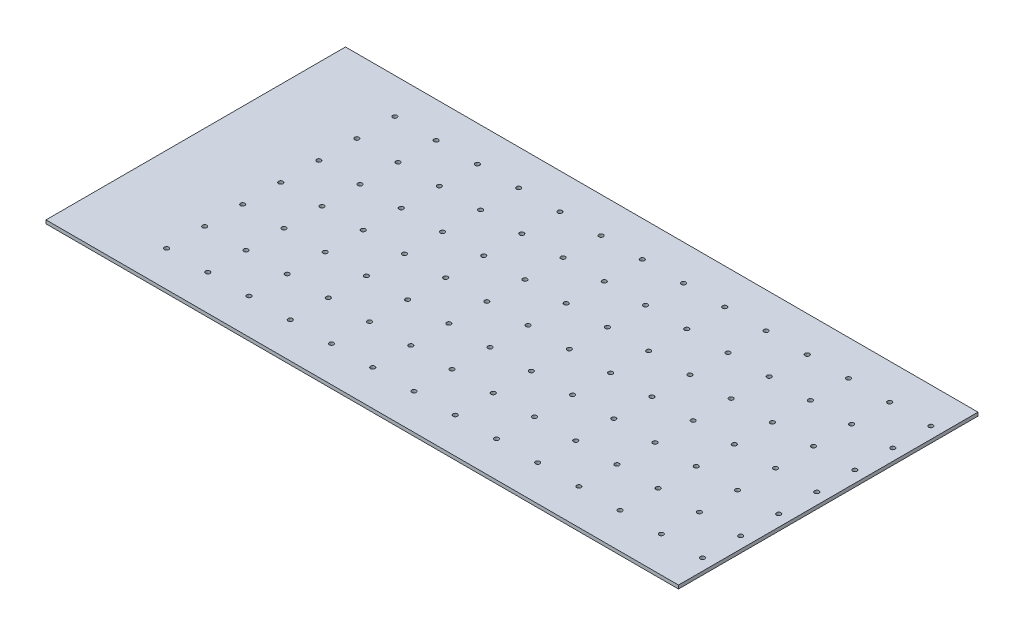
SolidWorks part; units mm, degrees
material "ABS PC"
ref_plane "Front Plane" through (0, 0, 0) normal (0, 0, 1) x (1, 0, 0)
ref_plane "Top Plane" through (0, 0, 0) normal (0, 1, 0) x (1, 0, 0)
ref_plane "Right Plane" through (0, 0, 0) normal (1, 0, 0) x (0, 0, -1)
sketch "Sketch1" plane through (0, 0, 0) normal (0, 1, 0) x (1, 0, 0)
  line L1 (-270, 129.32) -> (270, 129.32)
  line L2 (-270, 129.32) -> (-270, -129.32)
  line L3 (-270, -129.32) -> (270, -129.32)
  line L4 (270, 129.32) -> (270, -129.32)
  line L5 (-270, 129.32) -> (270, -129.32) construction
  line L6 (-270, -129.32) -> (270, 129.32) construction
  point P0 (0, 0)
  dimension "D1" = 540
  dimension "D2" = 258.64
extrude "Boss-Extrude1" add sketch "Sketch1" along normal blind 3.18
sketch "Sketch2" plane through (0, 3.18, 0) normal (0, 1, 0) x (1, 0, 0)
  line L0 (-270, 129.32) -> (-270, -129.32) construction
  line L1 (270, 129.32) -> (-270, 129.32) construction
  circle A0 centre (-232.08, 104.72) radius 2
  dimension "D1" = 4
  dimension "D2" = 37.92
  dimension "D3" = 24.6
extrude "Cut-Extrude1" cut sketch "Sketch2" against normal up to next
pattern_linear "LPattern1" count 14 spacing 37.81 along (1, 0, 0) count 7 spacing 34.9 along (0, 0, 1) of "Cut-Extrude1"
sketch "Sketch4" plane through (-270, 0, 0) normal (-1, 0, 0) x (0, 0, 1)
  line L1 (-129.32, 3.18) -> (129.32, 3.18)
  line L2 (-129.32, 3.18) -> (-129.32, 0)
  line L3 (-129.32, 0) -> (129.32, 0)
  line L4 (129.32, 3.18) -> (129.32, 0)
extrude "Boss-Extrude2" add sketch "Sketch4" along normal blind 40
sketch "Sketch5" plane through (0, 0, 129.32) normal (0, 0, 1) x (1, 0, 0)
  line L1 (270, 3.18) -> (-310, 3.18)
  line L2 (270, 3.18) -> (270, 0)
  line L3 (270, 0) -> (-310, 0)
  line L4 (-310, 3.18) -> (-310, 0)
extrude "Boss-Extrude3" add sketch "Sketch5" along normal blind 8
mirror "Mirror1" about plane through (0, 0, 0) normal (0, 0, 1) of "Boss-Extrude3"
